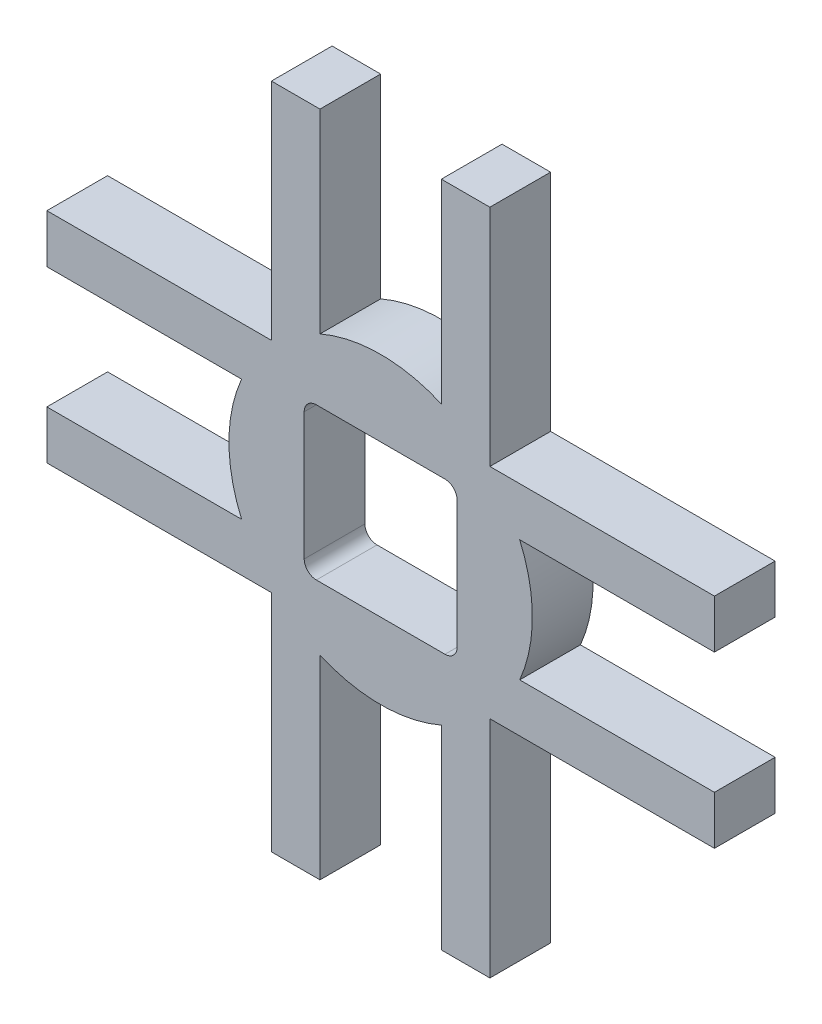
SolidWorks part; units mm, degrees
ref_plane "Front Plane" through (0, 0, 0) normal (0, 0, 1) x (1, 0, 0)
ref_plane "Top Plane" through (0, 0, 0) normal (0, 1, 0) x (1, 0, 0)
ref_plane "Right Plane" through (0, 0, 0) normal (1, 0, 0) x (0, 0, -1)
sketch "Sketch1" plane through (0, 0, 0) normal (0, 0, 1) x (1, 0, 0)
  circle A0 centre (0, 0) radius 12.5
  dimension "D2" = 25
extrude "Boss-Extrude1" add sketch "Sketch1" along normal mid plane 5
sketch "Sketch4" plane through (0, 0, 2.5) normal (0, 0, 1) x (1, 0, 0)
  line L0 (30.25, 0) -> (-30.25, 0) construction
  line L2 (-9, 0) -> (-5, 0)
  line L3 (0, 0) -> (0, 15.8331) construction
  line L4 (-9, 0) -> (-9, 27.5)
  line L5 (-9, 27.5) -> (-5, 27.5)
  line L6 (-5, 0) -> (-5, 27.5)
  line L7 (0, -30.25) -> (0, 30.25) construction
  line L8 (9, 27.5) -> (5, 27.5)
  line L9 (5, 0) -> (5, 27.5)
  line L10 (9, 0) -> (5, 0)
  line L11 (9, 0) -> (9, 27.5)
  dimension "D1" = 27.5
  dimension "D3" = 5
  dimension "D2" = 4
extrude "Boss-Extrude3" add sketch "Sketch4" against normal up to surface (5 mm away) up to face at (12.5, 0, -2.5)
pattern_circular "CirPattern7" count 4 over 360 about axis through (0, 0, 0) along (0, 0, 1) of "Boss-Extrude3"
sketch "Sketch7" plane through (-9, 0, 0) normal (-1, 0, 0) x (0, 0, 1)
  line L0 (-2.5, 27.5) -> (2.5, 27.5) construction
  line L1 (-2.5, 9) -> (-2.5, 27.5) construction
  circle A0 centre (5, 20) radius 1.45
  circle A1 centre (45, 20) radius 1.45
  circle A2 centre (85, 20) radius 1.45
  circle A3 centre (125, 20) radius 1.45
  circle A4 centre (165, 20) radius 1.45
  dimension "D1" = 2.9
  dimension "D2" = 7.5
  dimension "D3" = 7.5
  dimension "D4" = 5
sketch "Sketch10" plane through (0, 0, -2.5) normal (0, 0, -1) x (-1, 0, 0)
  circle A0 centre (0, 0) radius 12.5
  dimension "D1" = 25
sketch "Sketch8" plane through (0, 0, 2.5) normal (0, 0, 1) x (1, 0, 0)
  line L2 (-6.3, 6.25) -> (6.3, 6.25)
  line L3 (-6.3, 6.25) -> (-6.3, -6.25)
  line L4 (-6.3, -6.25) -> (6.3, -6.25)
  line L5 (6.3, 6.25) -> (6.3, -6.25)
  line L6 (-6.3, 6.25) -> (6.3, -6.25) construction
  line L7 (-6.3, -6.25) -> (6.3, 6.25) construction
  point P5 (0, 0)
  point P14 (0, 0)
  dimension "D1" = 12.6
  dimension "D2" = 12.5
extrude "Cut-Extrude3" cut sketch "Sketch8" against normal up to next
sketch "Sketch9" plane through (0, 0, 2.5) normal (0, 0, 1) x (1, 0, 0)
  line L0 (30.25, 0) -> (-30.25, 0) construction
  line L1 (6.3, -6.25) -> (6.3, 6.25) construction
  circle A0 centre (9.4, 0) radius 1.45
  circle A1 centre (0, -9.2875) radius 1.45
  circle A2 centre (-9.2875, 0.1125) radius 1.45
  circle A3 centre (0.1125, 9.4) radius 1.45
  point P14 (0.0562, 0.0563)
  dimension "D1" = 2.9
  dimension "D2" = 3.1
  dimension "D3" = 4
fillet "Fillet1" radius 1 4 edges at (-6.3, 6.25, 0) (6.3, 6.25, 0) (6.3, -6.25, 0) (-6.3, -6.25, 0)
equation "\"drumDiameter\"= 25"
equation "\"D2@Sketch1\"=\"drumDiameter\""
equation "\"drumLength\"= 5"
equation "\"D1@Sketch4\"=\"drumDiameter\"*(0.5+\"drumAbove\")"
equation "\"foamThickness\"= 10"
equation "\"D3@Sketch4\"=\"foamThickness\"/2"
equation "\"drumAbove\"= 0.6"
equation "\"D2@Sketch7\"=\"drumDiameter\"*\"drumAbove\"/2"
equation "\"holderThicc\"= 4"
equation "\"D2@Sketch4\"=\"holderThicc\""
equation "\"D1@Boss-Extrude1\"=\"drumLength\""
equation "\"squareBarLength\" = 12.6"
equation "\"D1@Sketch8\"=\"squareBarLength\""
equation "\"D2@Sketch9\"=(\"drumDiameter\"/2-\"squareBarLength\"/2)/2"
equation "\"D1@Sketch10\"=\"drumDiameter\""
equation "\"squareBarShortLen\" = 12.5"
equation "\"D2@Sketch8\"=\"squareBarShortLen\""
